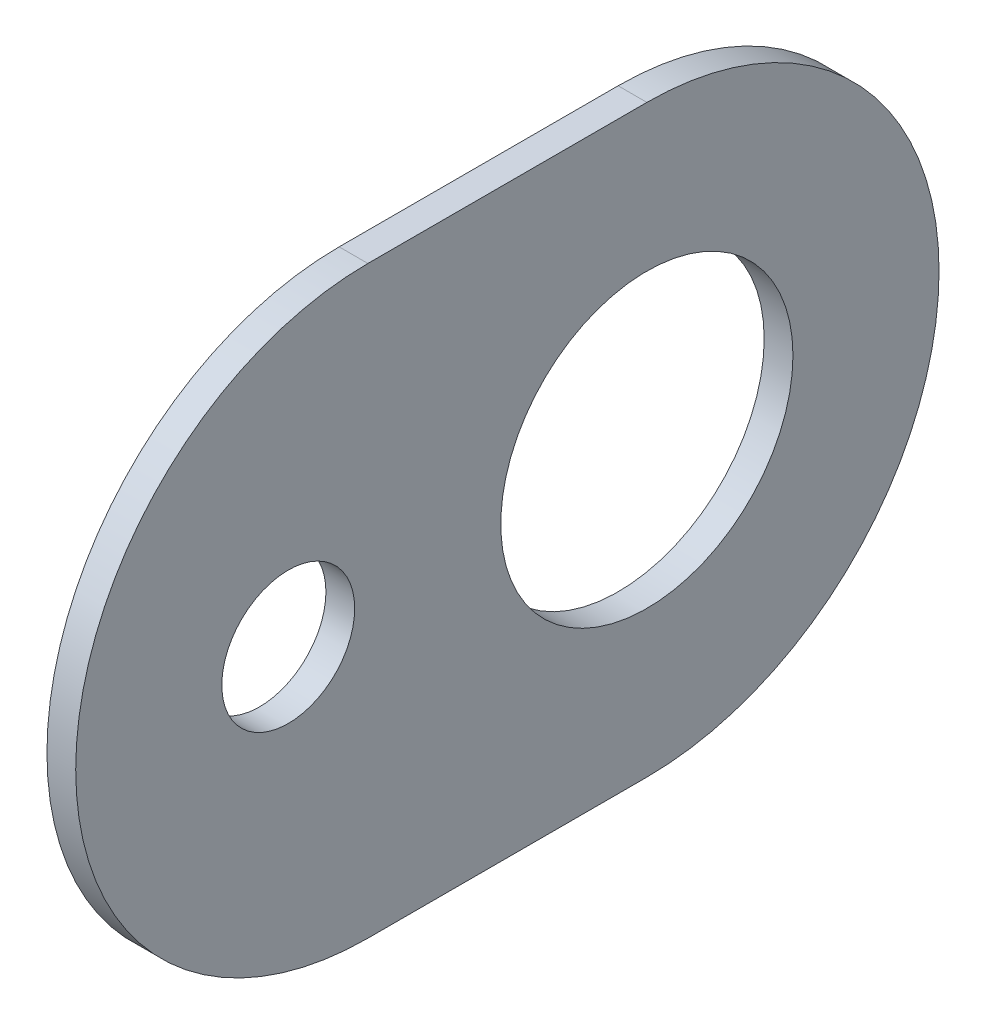
SolidWorks part; units mm, degrees
material "Ti-6Al-4VSolution treated and aged (SS)"
ref_plane "Front Plane" through (0, 0, 0) normal (1, 0, 0) x (0, 1, 0)
ref_plane "Top Plane" through (0, 0, 0) normal (0, 0, 1) x (0, 1, 0)
ref_plane "Right Plane" through (0, 0, 0) normal (0, 1, 0) x (-1, 0, 0)
sketch "Sketch1" plane through (0, 0, 0) normal (1, 0, 0) x (0, 1, 0)
  line L0 (0, -12.126) -> (0, 12.126) construction
  line L1 (-25.4, -12.126) -> (-25.4, 12.126)
  line L2 (25.4, -12.126) -> (25.4, 12.126)
  line L3 (0, 24.826) -> (0, 37.526) construction
  line L4 (0, 37.526) -> (0, -24.826) construction
  line L5 (0, -24.826) -> (0, -37.526) construction
  line L6 (12.7, -12.126) -> (25.4, -12.126) construction
  arc A0 (-25.4, -12.126) -> (25.4, -12.126) centre (0, -12.126) ccw
  arc A1 (25.4, 12.126) -> (-25.4, 12.126) centre (0, 12.126) ccw
  circle A2 centre (0, 19.05) radius 5.776
  circle A3 centre (0, -12.126) radius 12.7
  point P2 (0, 0)
  point P18 (0, 13.274)
  point P19 (0, 0.574)
  point P25 (0, 0)
  point P27 (13.851, 18.449)
  point P28 (15.1813, 20.5803)
  dimension "D1" = 25.4
  dimension "D2" = 11.5519
  dimension "D3" = 12.7
  dimension "D4" = 12.7
  dimension "D5" = 12.7
  dimension "D6" = 12.7
extrude "Boss-Extrude1" add sketch "Sketch1" along normal blind 2.5
equation "\"E\"= 15199999.87'Titainium Grade 5 Modulus of Elasticity"
equation "\"s\"= 120000.0006'Titanium Grade 5 Yield strength"
equation "\"dmax\"= 0.005'maximum allowable deflection"
equation "\"F\"= 750'Load"
equation "\"Sf\" = 4'Safety Factor"
equation "\"cxs\"= ( \"F\" * \"Sf\" ) / ( \"s\" * 0.05 ) 'Minimum material edge to edge length"
equation "\"Lmin\"= ( \"cxs\" * 3 ) + 1.0005 + 0.6643 'Maximum Length"
equation "\"Lmax\"= ( \"cxs\" * 3 ) + 1.000 + 0.6633'Minimum Length"
equation "\"Lavg\"= 0.5 * ( \"Lmin\" + \"Lmax\" )'Average Length"
equation "\"D3@Sketch1\"=\"cxs\""
equation "\"D4@Sketch1\"=\"cxs\""
equation "\"D5@Sketch1\"= \"cxs\""
equation "\"D6@Sketch1\"=\"cxs\""
